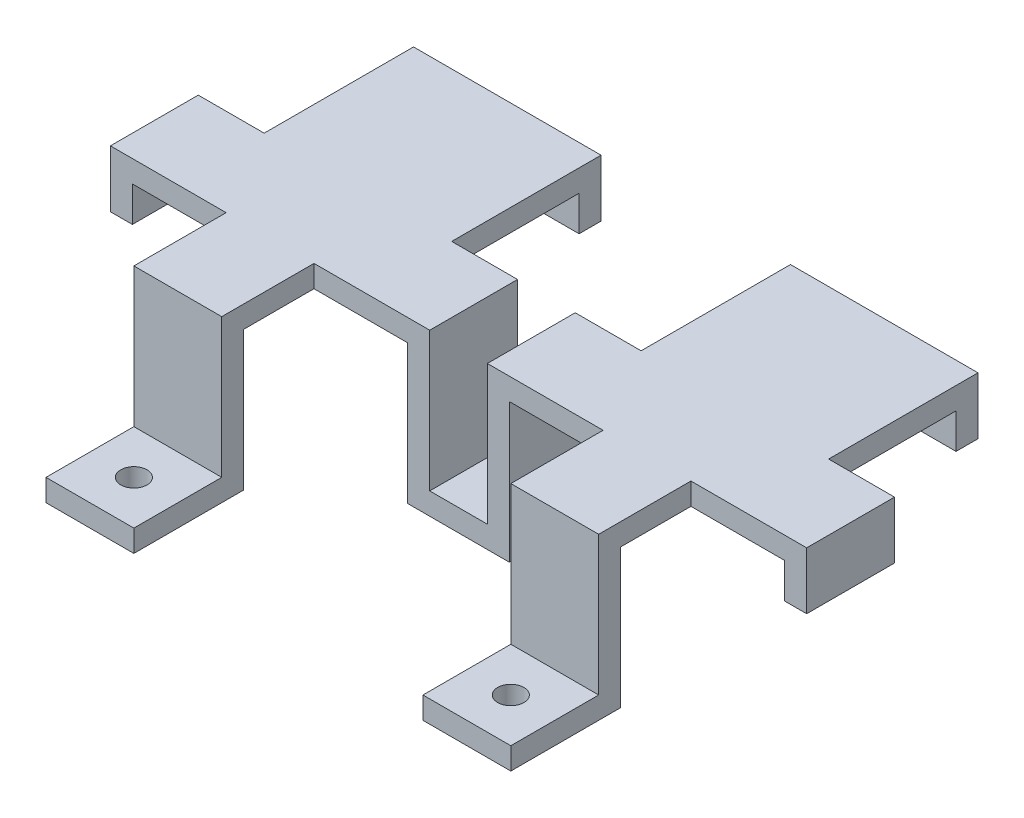
SolidWorks part; units mm, degrees
material "Custom Plastic"
ref_plane "Front Plane" through (0, 0, 0) normal (0, 0, 1) x (1, 0, 0)
ref_plane "Top Plane" through (0, 0, 0) normal (0, 1, 0) x (1, 0, 0)
ref_plane "Right Plane" through (0, 0, 0) normal (1, 0, 0) x (0, 0, -1)
sketch "Sketch1" plane through (0, 0, 0) normal (0, 1, 0) x (1, 0, 0)
  line L1 (-50.3174, -6.35) -> (50.3174, -6.35)
  line L2 (-50.3174, -6.35) -> (-50.3174, 6.35)
  line L3 (-50.3174, 6.35) -> (50.3174, 6.35)
  line L4 (50.3174, -6.35) -> (50.3174, 6.35)
  line L5 (-50.3174, -6.35) -> (50.3174, 6.35) construction
  line L6 (-50.3174, 6.35) -> (50.3174, -6.35) construction
  point P0 (0, 0)
  dimension "D1" = 12.7
  dimension "D2" = 100.6348
extrude "Boss-Extrude1" add sketch "Sketch1" along normal blind 3.175
sketch "Sketch2" plane through (0, 0, 0) normal (0, -1, 0) x (1, 0, 0)
  line L0 (50.3174, -6.35) -> (-50.3174, -6.35) construction
  line L1 (-50.3174, 6.35) -> (-47.1424, 6.35)
  line L2 (-50.3174, 6.35) -> (-50.3174, -6.35)
  line L3 (-50.3174, -6.35) -> (-47.1424, -6.35)
  line L4 (-47.1424, 6.35) -> (-47.1424, -6.35)
  line L6 (50.3174, 6.35) -> (47.1424, 6.35)
  line L7 (50.3174, 6.35) -> (50.3174, -6.35)
  line L8 (50.3174, -6.35) -> (47.1424, -6.35)
  line L9 (47.1424, 6.35) -> (47.1424, -6.35)
  dimension "D1" = 3.175
extrude "Boss-Extrude2" add sketch "Sketch2" along normal blind 5.08
sketch "Sketch3" plane through (0, 0, 0) normal (0, -1, 0) x (1, 0, 0)
  line L0 (0, 6.35) -> (0, -6.35) construction
  line L1 (-47.1424, 6.35) -> (47.1424, 6.35) construction
  line L2 (47.1424, -6.35) -> (-47.1424, -6.35) construction
  line L4 (-7.3406, 6.35) -> (7.3406, 6.35)
  line L5 (-7.3406, 6.35) -> (-7.3406, -6.35)
  line L6 (-7.3406, -6.35) -> (7.3406, -6.35)
  line L7 (7.3406, 6.35) -> (7.3406, -6.35)
  dimension "D1" = 14.6812
extrude "Boss-Extrude3" add sketch "Sketch3" along normal blind 20.1168
sketch "Sketch4" plane through (0, 0, 6.35) normal (0, 0, 1) x (1, 0, 0)
  line L0 (-50.3174, 3.175) -> (50.3174, 3.175) construction
  line L1 (-4.1656, 3.175) -> (4.1656, 3.175)
  line L2 (-4.1656, 3.175) -> (-4.1656, -16.9418)
  line L3 (-4.1656, -16.9418) -> (4.1656, -16.9418)
  line L4 (4.1656, 3.175) -> (4.1656, -16.9418)
  line L5 (0, 3.175) -> (0, -20.1168) construction
  line L6 (7.3406, -20.1168) -> (-7.3406, -20.1168) construction
  line L7 (7.3406, -20.1168) -> (7.3406, 0) construction
  dimension "D1" = 3.175
  dimension "D2" = 3.175
extrude "Cut-Extrude1" cut sketch "Sketch4" against normal blind 20.1168
sketch "Sketch5" plane through (0, 0, 0) normal (0, -1, 0) x (1, 0, 0)
  line L0 (-7.3406, -6.35) -> (-47.1424, -6.35) construction
  line L1 (-40.7924, -6.35) -> (-13.6906, -6.35)
  line L2 (-40.7924, -6.35) -> (-40.7924, -27.94)
  line L3 (-40.7924, -27.94) -> (-13.6906, -27.94)
  line L4 (-13.6906, -6.35) -> (-13.6906, -27.94)
  line L5 (0, 6.35) -> (0, -6.35) construction
  line L6 (7.3406, 6.35) -> (-7.3406, 6.35) construction
  line L7 (-7.3406, -6.35) -> (7.3406, -6.35) construction
  line L8 (-7.3406, 6.35) -> (-7.3406, -6.35) construction
  line L9 (-47.1424, -6.35) -> (-47.1424, 6.35) construction
  line L10 (13.6906, -6.35) -> (13.6906, -27.94)
  line L11 (40.7924, -27.94) -> (13.6906, -27.94)
  line L12 (40.7924, -6.35) -> (40.7924, -27.94)
  line L13 (40.7924, -6.35) -> (13.6906, -6.35)
  dimension "D1" = 21.59
  dimension "D2" = 6.35
  dimension "D3" = 6.35
extrude "Boss-Extrude4" add sketch "Sketch5" against normal up to surface (3.175 mm away) up to face at (-27.2415, 3.175, 0)
sketch "Sketch6" plane through (0, 0, 0) normal (0, -1, 0) x (1, 0, 0)
  line L0 (-13.6906, -27.94) -> (-13.6906, -6.35) construction
  line L1 (-40.7924, -27.94) -> (-13.6906, -27.94)
  line L2 (-40.7924, -27.94) -> (-40.7924, -24.765)
  line L3 (-40.7924, -24.765) -> (-13.6906, -24.765)
  line L4 (-13.6906, -27.94) -> (-13.6906, -24.765)
  line L5 (40.7924, -27.94) -> (40.7924, -6.35) construction
  line L6 (13.6906, -27.94) -> (40.7924, -27.94)
  line L7 (13.6906, -27.94) -> (13.6906, -24.765)
  line L8 (13.6906, -24.765) -> (40.7924, -24.765)
  line L9 (40.7924, -27.94) -> (40.7924, -24.765)
  dimension "D1" = 3.175
extrude "Boss-Extrude5" add sketch "Sketch6" along normal blind 5.08
sketch "Sketch7" plane through (0, 0, 0) normal (0, -1, 0) x (1, 0, 0)
  line L0 (-47.1424, 6.35) -> (-7.3406, 6.35) construction
  line L1 (-33.5915, 6.35) -> (-20.8915, 6.35)
  line L2 (-33.5915, 6.35) -> (-33.5915, 19.685)
  line L3 (-33.5915, 19.685) -> (-20.8915, 19.685)
  line L4 (-20.8915, 6.35) -> (-20.8915, 19.685)
  line L5 (-13.6906, -24.765) -> (-40.7924, -24.765) construction
  line L6 (0, 6.35) -> (0, -6.35) construction
  line L7 (7.3406, 6.35) -> (-7.3406, 6.35) construction
  line L8 (-7.3406, -6.35) -> (7.3406, -6.35) construction
  line L9 (-27.2415, -24.765) -> (-27.2415, 6.35) construction
  line L10 (20.8915, 6.35) -> (20.8915, 19.685)
  line L11 (33.5915, 19.685) -> (20.8915, 19.685)
  line L12 (33.5915, 6.35) -> (33.5915, 19.685)
  line L13 (33.5915, 6.35) -> (20.8915, 6.35)
  dimension "D1" = 44.45
  dimension "D2" = 12.7
extrude "Boss-Extrude6" add sketch "Sketch7" against normal up to surface (3.175 mm away) up to face at (27.2415, 3.175, -8.5725)
sketch "Sketch8" plane through (0, 0, 0) normal (0, -1, 0) x (1, 0, 0)
  line L0 (-20.8915, 6.35) -> (-20.8915, 19.685) construction
  line L1 (-33.5915, 19.685) -> (-20.8915, 19.685)
  line L2 (-33.5915, 19.685) -> (-33.5915, 16.51)
  line L3 (-33.5915, 16.51) -> (-20.8915, 16.51)
  line L4 (-20.8915, 19.685) -> (-20.8915, 16.51)
  line L5 (0, -6.35) -> (0, 6.35) construction
  line L6 (-7.3406, -6.35) -> (7.3406, -6.35) construction
  line L7 (7.3406, 6.35) -> (-7.3406, 6.35) construction
  line L8 (20.8915, 19.685) -> (20.8915, 16.51)
  line L9 (33.5915, 16.51) -> (20.8915, 16.51)
  line L10 (33.5915, 19.685) -> (33.5915, 16.51)
  line L11 (33.5915, 19.685) -> (20.8915, 19.685)
  dimension "D1" = 3.175
extrude "Boss-Extrude7" add sketch "Sketch8" along normal up to surface (20.1168 mm away) up to face at (0, -20.1168, 0)
sketch "Sketch9" plane through (0, 0, 19.685) normal (0, 0, 1) x (1, 0, 0)
  line L0 (-20.8915, 3.175) -> (-20.8915, -20.1168) construction
  line L1 (-33.5915, -20.1168) -> (-20.8915, -20.1168)
  line L2 (-33.5915, -20.1168) -> (-33.5915, -16.9418)
  line L3 (-33.5915, -16.9418) -> (-20.8915, -16.9418)
  line L4 (-20.8915, -20.1168) -> (-20.8915, -16.9418)
  line L5 (0, -20.1168) -> (0, -16.9418) construction
  line L6 (7.3406, -20.1168) -> (-7.3406, -20.1168) construction
  line L7 (-4.1656, -16.9418) -> (4.1656, -16.9418) construction
  line L8 (20.8915, -20.1168) -> (20.8915, -16.9418)
  line L9 (33.5915, -16.9418) -> (20.8915, -16.9418)
  line L10 (33.5915, -20.1168) -> (33.5915, -16.9418)
  line L11 (33.5915, -20.1168) -> (20.8915, -20.1168)
  dimension "D1" = 3.175
extrude "Boss-Extrude8" add sketch "Sketch9" along normal blind 12.7
sketch "Sketch10" plane through (0, 0, -6.35) normal (0, 0, -1) x (-1, 0, 0)
  line L0 (7.3406, -20.1168) -> (7.3406, 0) construction
  line L1 (-7.3406, -20.1168) -> (7.3406, -20.1168)
  line L2 (-7.3406, -20.1168) -> (-7.3406, -16.9418)
  line L3 (-7.3406, -16.9418) -> (7.3406, -16.9418)
  line L4 (7.3406, -20.1168) -> (7.3406, -16.9418)
  line L5 (4.1656, -16.9418) -> (-4.1656, -16.9418) construction
extrude "Boss-Extrude9" add sketch "Sketch10" along normal blind 12.7
hole_wizard "#6 Clearance Hole1" positions "3DSketch1" profile "Sketch11" hole size "#6" standard "ANSI Inch" end condition through all
sketch3d "3DSketch1"
  line L0 (0, -16.9418, -19.05) -> (0, -16.9418, 6.35) construction
  line L1 (-7.3406, -16.9418, -19.05) -> (7.3406, -16.9418, -19.05) construction
  line L2 (-4.1656, -16.9418, 6.35) -> (4.1656, -16.9418, 6.35) construction
  line L4 (-20.8915, -16.9418, 19.685) -> (-33.5915, -16.9418, 32.385) construction
  line L5 (20.8915, -16.9418, 32.385) -> (33.5915, -16.9418, 19.685) construction
  point P0 (0, -16.9418, -12.7)
  point P2 (-27.2415, -16.9418, 26.035)
  point P4 (27.2415, -16.9418, 26.035)
  point P23 (0, 0, 0)
  point P24 (0, 0, 0)
  point P25 (0, 0, 0)
  dimension "D1" = 6.35
sketch "Sketch11" plane through (0, -16.9418, -12.7) normal (1, 0, 0) x (0, 0, 1)
  line L0 (0, 0) -> (0, 3.175)
  line L1 (0, 3.175) -> (1.8986, 3.175)
  line L2 (1.8986, 3.175) -> (1.8986, 0)
  line L5 (1.8986, 0) -> (0, 0)
  line L11 (0, -6.35) -> (0, 107.95) construction
  dimension "Thru Hole Dia." = 3.7973
  dimension "Thru Hole Depth" = 3.175
